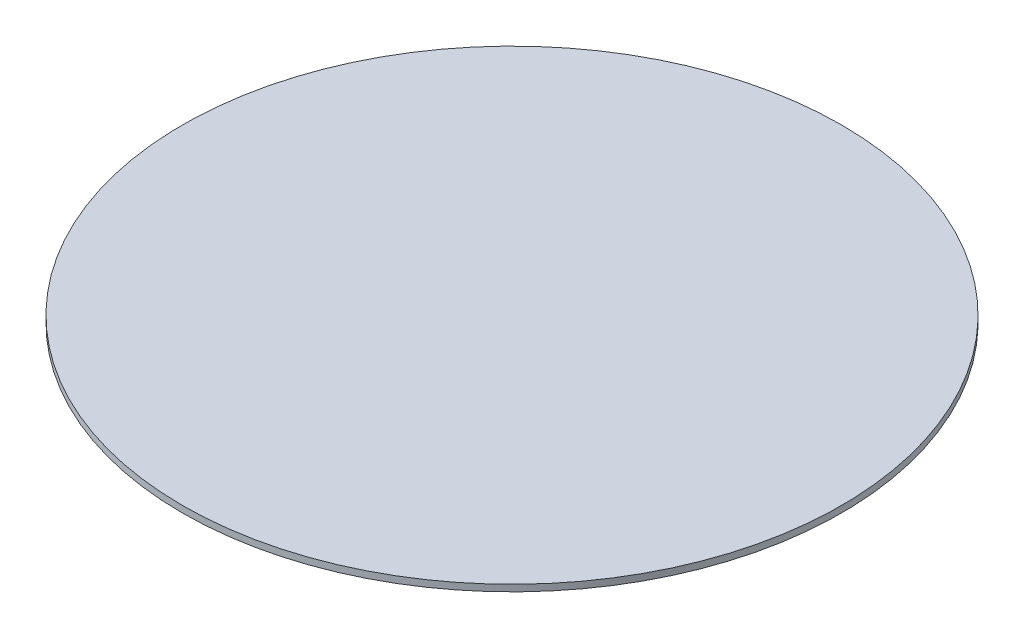
SolidWorks part; units mm, degrees
ref_plane "Front Plane" through (0, 0, 0) normal (0, 0, 1) x (1, 0, 0)
ref_plane "Top Plane" through (0, 0, 0) normal (0, 1, 0) x (1, 0, 0)
ref_plane "Right Plane" through (0, 0, 0) normal (1, 0, 0) x (0, 0, -1)
sketch "Sketch1" plane through (0, 0, 0) normal (0, 1, 0) x (1, 0, 0)
  circle A0 centre (0, 0) radius 300
  dimension "D1" = 600
extrude "Boss-Extrude1" add sketch "Sketch1" along normal blind 6
